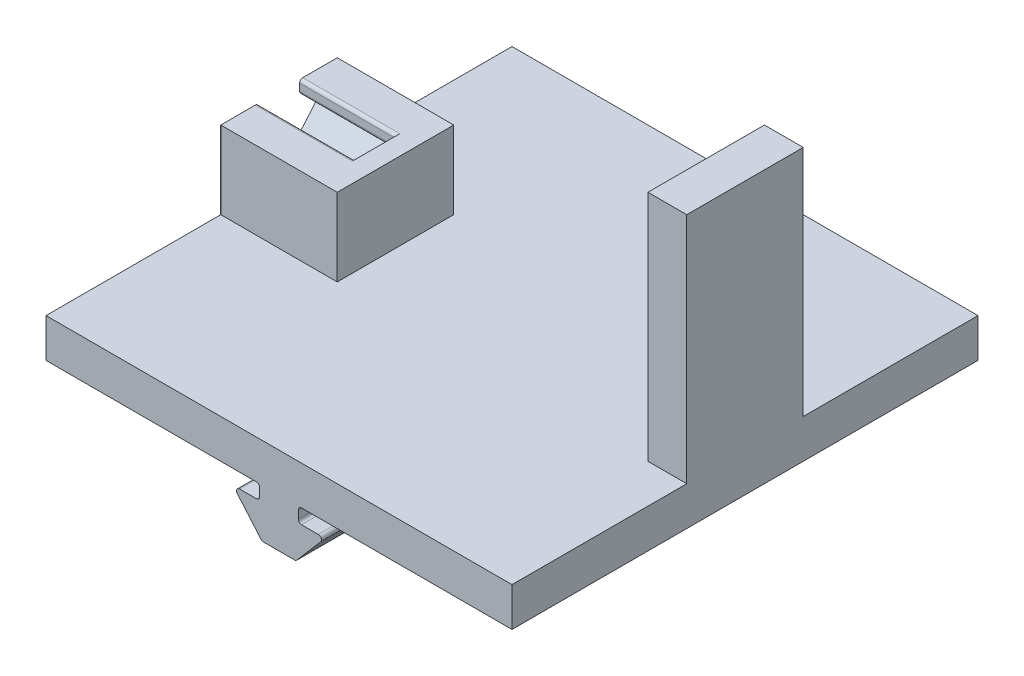
SolidWorks part; units mm, degrees
ref_plane "Front Plane" through (0, 0, 0) normal (0, 0, 1) x (1, 0, 0)
ref_plane "Top Plane" through (0, 0, 0) normal (0, 1, 0) x (1, 0, 0)
ref_plane "Right Plane" through (0, 0, 0) normal (1, 0, 0) x (0, 0, -1)
sketch "Sketch1" plane through (0, 0, 0) normal (0, 0, 1) x (1, 0, 0)
  line L1 (-38.1, 6.35) -> (38.1, 6.35)
  line L2 (-38.1, 6.35) -> (-38.1, 0)
  line L3 (-38.1, 0) -> (38.1, 0)
  line L4 (38.1, 6.35) -> (38.1, 0)
  point P4 (0, 0)
  point P6 (21.2452, 8.5644)
  point P7 (38.0839, 8.0958)
  point P9 (-37.5696, 6.35)
  dimension "D1" = 76.2
  dimension "D2" = 6.35
extrude "Boss-Extrude1" add sketch "Sketch1" along normal mid plane 76.2
sketch "Sketch2" plane through (0, 0, 0) normal (0, 0, 1) x (1, 0, 0)
  line L1 (-38.1, 6.35) -> (-19.05, 6.35)
  line L2 (-38.1, 6.35) -> (-38.1, 19.05)
  line L3 (-38.1, 19.05) -> (-19.05, 19.05)
  line L4 (-19.05, 6.35) -> (-19.05, 19.05)
  line L5 (38.1, 6.35) -> (31.75, 6.35)
  line L6 (38.1, 6.35) -> (38.1, 44.45)
  line L7 (38.1, 44.45) -> (31.75, 44.45)
  line L8 (31.75, 6.35) -> (31.75, 44.45)
  dimension "D1" = 6.35
  dimension "D2" = 38.1
  dimension "D3" = 19.05
  dimension "D4" = 12.7
extrude "Boss-Extrude2" add sketch "Sketch2" along normal mid plane 19.05
sketch "Sketch3" plane through (0, 0, 0) normal (0, 0, 1) x (1, 0, 0)
  line L0 (-3.175, 0) -> (-3.175, -2.3813)
  line L1 (-38.1, 0) -> (38.1, 0) construction
  line L2 (-3.175, -2.3813) -> (-7.5406, -2.3813)
  line L3 (-7.5406, -2.3813) -> (-2.7781, -7.9375)
  line L4 (-2.7781, -7.9375) -> (2.7781, -7.9375)
  line L5 (2.7781, -7.9375) -> (7.5406, -2.3812)
  line L6 (7.5406, -2.3812) -> (3.175, -2.3812)
  line L7 (3.175, -2.3812) -> (3.175, 0)
  line L8 (3.175, 0) -> (-3.175, 0)
  point P10 (0, 0)
  point P11 (0, -7.9375)
  point P13 (4.2959, -9.4318)
  point P14 (14.0593, -5.8388)
  point P15 (2.9681, -13.8839)
  point P16 (14.0593, -5.9531)
  point P17 (5.2622, -5.0635)
  point P18 (1.5767, -3.9198)
  dimension "D1" = 6.35
  dimension "D2" = 15.0812
  dimension "D3" = 2.3813
  dimension "D4" = 5.5562
  dimension "D5" = 5.5562
extrude "Boss-Extrude3" add sketch "Sketch3" along normal up to surface and the other way up to surface up to face at (0, 3.175, 38.1) other way up to face at (0, 3.175, -38.1)
sketch "Sketch5" plane through (0, 0, 0) normal (-1, 0, 0) x (0, 0, 1)
  line L0 (-3.175, 19.05) -> (-3.175, 16.6688) construction
  line L1 (-3.175, 16.6688) -> (-7.5406, 16.6688) construction
  line L2 (-7.5406, 16.6688) -> (-2.7781, 11.1125) construction
  line L3 (-2.7781, 11.1125) -> (2.7781, 11.1125) construction
  line L4 (2.7781, 11.1125) -> (7.5406, 16.6688) construction
  line L5 (7.5406, 16.6688) -> (3.175, 16.6688) construction
  line L6 (3.175, 16.6688) -> (3.175, 19.05) construction
  line L7 (3.175, 19.05) -> (-3.175, 19.05) construction
  line L8 (9.525, 19.05) -> (-9.525, 19.05) construction
  line L9 (-3.375, 19.05) -> (-3.375, 16.8688)
  line L10 (-3.375, 16.8688) -> (-7.9755, 16.8688)
  line L11 (-7.9755, 16.8688) -> (-2.8701, 10.9125)
  line L12 (-2.8701, 10.9125) -> (2.8701, 10.9125)
  line L13 (2.8701, 10.9125) -> (7.9755, 16.8688)
  line L14 (7.9755, 16.8688) -> (3.375, 16.8688)
  line L15 (3.375, 16.8688) -> (3.375, 19.05)
  line L16 (-3.375, 19.05) -> (3.375, 19.05)
  point P9 (0, 11.1125)
  point P11 (0, 19.05)
  dimension "D1" = 6.35
  dimension "D2" = 15.0812
  dimension "D3" = 2.3813
  dimension "D4" = 5.5562
  dimension "D5" = 5.5562
  dimension "D6" = 0.2
extrude "Cut-Extrude2" cut sketch "Sketch5" against normal offset from surface (15.875 mm away) 3.175 from surface at 38.1 up to face at (-19.05, 12.7, 0) starting at face at (-38.1, 7.9375, 0)
fillet "Fillet1" radius 0.508 16 edges at (-7.5406, -2.3813, 0) (-2.7781, -7.9375, 0) (2.7781, -7.9375, 0) (7.5406, -2.3813, 0) (3.175, -2.3812, 0) (-3.175, -2.3813, 0) (-3.175, 0, 0) (3.175, 0, 0) (-30.1625, 19.05, -3.375) (-30.1625, 19.05, 3.375) (-30.1625, 10.9125, -2.8701) (-30.1625, 10.9125, 2.8701) (-30.1625, 16.8688, 7.9755) (-30.1625, 16.8688, -7.9755) (-30.1625, 16.8688, -3.375) (-30.1625, 16.8688, 3.375)
